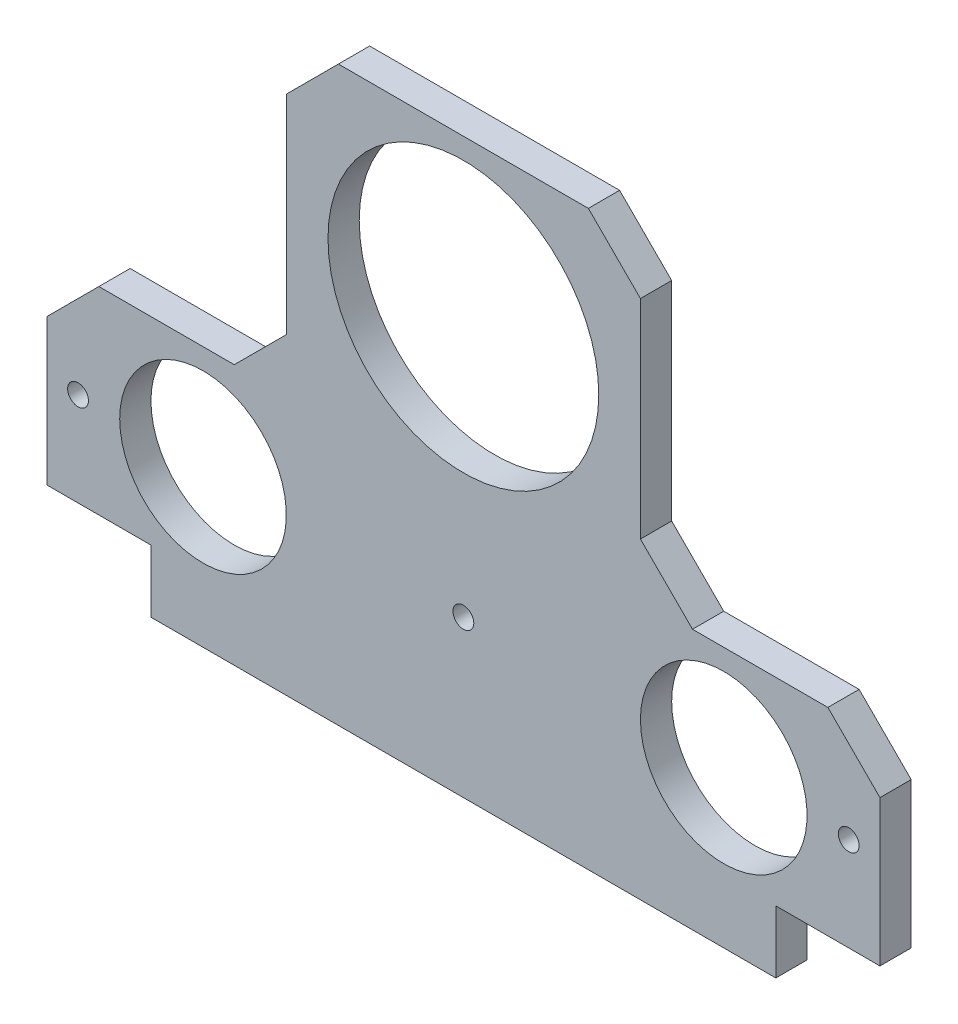
SolidWorks part; units mm, degrees
ref_plane "Plan de face" through (0, 0, 0) normal (0, 0, 1) x (1, 0, 0)
ref_plane "Plan de dessus" through (0, 0, 0) normal (0, 1, 0) x (1, 0, 0)
ref_plane "Plan de droite" through (0, 0, 0) normal (1, 0, 0) x (0, 0, -1)
sketch "Esquisse1" plane through (0, 0, 0) normal (0, 0, 1) x (1, 0, 0)
  line L0 (0, 0) -> (0, 55) construction
  line L1 (-40, 0) -> (40, 0)
  line L2 (40, 0) -> (40, 25)
  line L3 (40, 25) -> (17, 25)
  line L4 (17, 25) -> (17, 55)
  line L5 (17, 55) -> (-17, 55)
  line L6 (-17, 25) -> (-17, 55)
  line L7 (-40, 25) -> (-17, 25)
  line L8 (-40, 0) -> (-40, 25)
  line L9 (17, 40) -> (0, 40) construction
  circle A0 centre (0, 40) radius 13
  dimension "D4" = 26
  dimension "D5" = 40
  dimension "D1" = 80
  dimension "D2" = 34
  dimension "D3" = 30
extrude "Boss.-Extru.1" add sketch "Esquisse1" along normal blind 12
sketch "Esquisse2" plane through (0, 0, 12) normal (0, 0, 1) x (1, 0, 0)
  circle A0 centre (0, 40) radius 13
  circle A1 centre (0, 40) radius 5.5
  dimension "D1" = 26
  dimension "D2" = 11
extrude "Boss.-Extru.2" add sketch "Esquisse2" along normal blind 3 from vertex at -12 starting at point (17, 55, 0)
sketch "Esquisse4" plane through (0, 0, 0) normal (0, 0, -1) x (-1, 0, 0)
  line L0 (0, 0) -> (0, 55) construction
  line L1 (-17, 55) -> (17, 55) construction
  line L3 (40, 0) -> (-40, 0) construction
  line L4 (-40, 0) -> (-40, 25) construction
  circle A0 centre (-25, 15) radius 8
  circle A1 centre (25, 15) radius 8
  dimension "D1" = 16
  dimension "D2" = 15
  dimension "D3" = 15
extrude "Enlèv. mat.-Extru.2" cut sketch "Esquisse4" against normal blind 6
sketch "Esquisse5" plane through (0, 0, 6) normal (0, 0, -1) x (-1, 0, 0)
  line L0 (0, 0) -> (0, 55) construction
  line L1 (40, 0) -> (-40, 0) construction
  line L2 (-17, 55) -> (17, 55) construction
  circle A0 centre (-25, 15) radius 3
  circle A1 centre (25, 15) radius 3
  dimension "D1" = 6
extrude "Enlèv. mat.-Extru.3" cut sketch "Esquisse5" against normal through all
sketch "Esquisse6" plane through (0, 0, 12) normal (0, 0, 1) x (1, 0, 0)
  line L0 (0, 0) -> (0, 7.1495) construction
  line L1 (30, 0) -> (30, 6)
  line L2 (-40, 0) -> (-30, 0)
  line L3 (-40, 0) -> (-40, 6)
  line L4 (-40, 6) -> (-30, 6)
  line L5 (-30, 0) -> (-30, 6)
  line L6 (40, 6) -> (30, 6)
  line L7 (40, 0) -> (40, 6)
  line L8 (40, 0) -> (30, 0)
  dimension "D1" = 6
  dimension "D2" = 10
extrude "Enlèv. mat.-Extru.4" cut sketch "Esquisse6" against normal up to vertex
chamfer "Chanfrein1" distance 5 angle 45 6 edges at (40, 25, 6) (17, 25, 6) (-17, 25, 6) (-40, 25, 6) (17, 55, 6) (-17, 55, 6)
sketch "Esquisse7" plane through (0, 0, 0) normal (0, 0, -1) x (-1, 0, 0)
  line L0 (0, 0) -> (0, 55) construction
  line L1 (-12, 55) -> (12, 55) construction
  line L2 (0, 15) -> (-37, 15) construction
  line L3 (30, 0) -> (-30, 0) construction
  circle A0 centre (-10, 45) radius 1
  circle A1 centre (10, 45) radius 1
  circle A2 centre (-37, 15) radius 1
  circle A3 centre (37, 15) radius 1
  circle A4 centre (0, 15) radius 1
  dimension "D3" = 2
  dimension "D1" = 10
  dimension "D2" = 10
  dimension "D4" = 15
  dimension "D5" = 37
extrude "Enlèv. mat.-Extru.5" cut sketch "Esquisse7" against normal up to vertex (12 mm away) up to point (-35, 25, 12)
sketch "Esquisse8" plane through (0, 55, 0) normal (0, 1, 0) x (1, 0, 0)
  line L0 (40, 0) -> (40, -12) construction
  line L1 (-40, 0) -> (40, 0)
  line L2 (-40, 0) -> (-40, -3)
  line L3 (-40, -3) -> (40, -3)
  line L4 (40, 0) -> (40, -3)
  line L5 (40, -12) -> (35, -12) construction
  line L7 (-40, -12) -> (40, -12)
  line L8 (-40, -12) -> (-40, -6)
  line L9 (-40, -6) -> (40, -6)
  line L10 (40, -12) -> (40, -6)
  dimension "D1" = 9
  dimension "D2" = 3
extrude "Enlèv. mat.-Extru.6" cut sketch "Esquisse8" against normal through all
